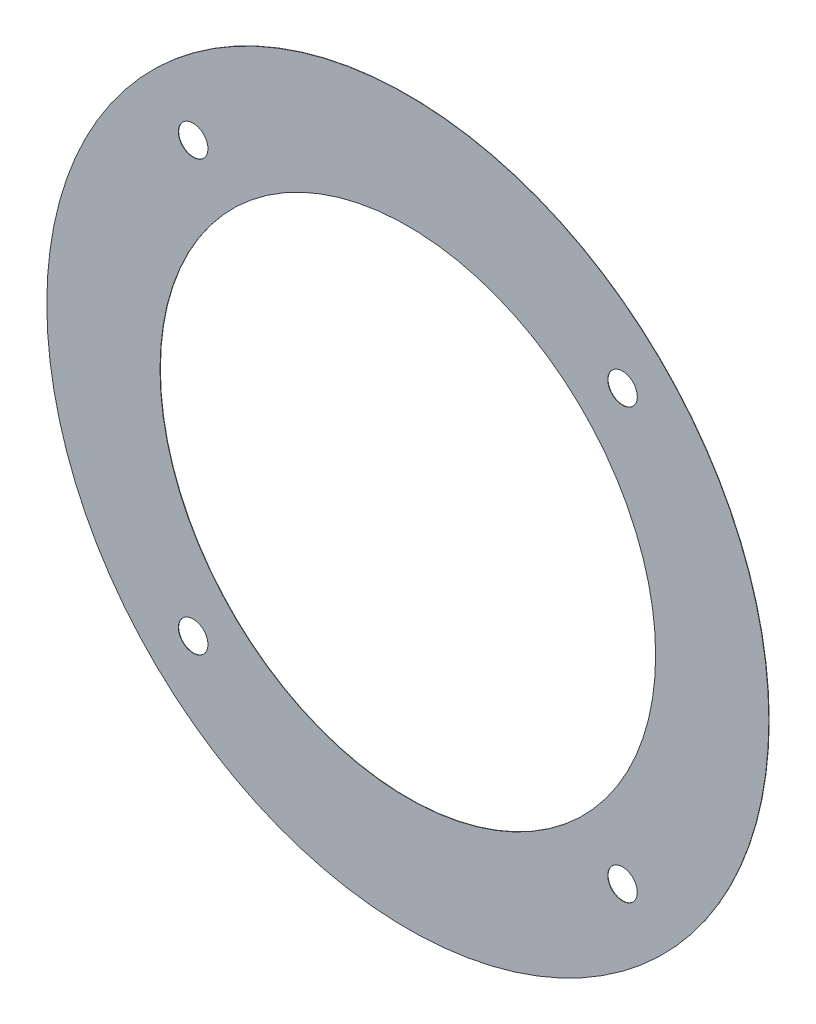
SolidWorks part; units mm, degrees
ref_plane "Piano frontale" through (0, 0, 0) normal (0, 0, 1) x (1, 0, 0)
ref_plane "Piano superiore" through (0, 0, 0) normal (0, 1, 0) x (1, 0, 0)
ref_plane "Piano destro" through (0, 0, 0) normal (1, 0, 0) x (0, 0, -1)
sketch "Schizzo1" plane through (0, 0, 0) normal (0, 0, 1) x (1, 0, 0)
  circle A0 centre (0, 0) radius 110
  circle A1 centre (0, 0) radius 75.5
  dimension "D1" = 151
  dimension "D2" = 220
extrude "Estrusione-Estrusione1" add sketch "Schizzo1" along normal blind 0.1
sketch "Schizzo2" plane through (0, 0, 0.1) normal (0, 0, 1) x (1, 0, 0)
  line L0 (0, 0) -> (0, 131.6623) construction
  line L1 (0, 0) -> (-120.2444, 120.2444) construction
  circle A0 centre (0, 0) radius 92.5
  dimension "D2" = 185
  dimension "D1" = 45
sketch "Schizzo3" plane through (0, 0, 0.1) normal (0, 0, 1) x (1, 0, 0)
  line L0 (0, 0) -> (-120.2444, 120.2444) construction
  circle A0 centre (-65.4074, 65.4074) radius 4.5
  circle A1 centre (0, 0) radius 92.5 construction
  circle A2 centre (65.4074, 65.4074) radius 4.5
  circle A3 centre (65.4074, -65.4074) radius 4.5
  circle A4 centre (-65.4074, -65.4074) radius 4.5
  point P15 (0, 0)
  dimension "D1" = 9
  dimension "D2" = 4
extrude "Taglio-Estrusione1" cut sketch "Schizzo3" against normal through all
